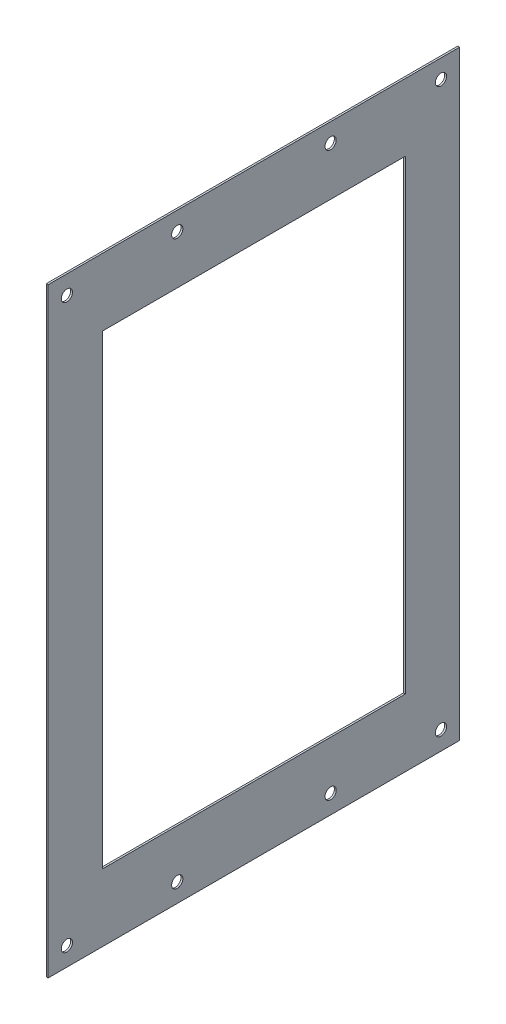
SolidWorks part; units mm, degrees
ref_plane "Front Plane" through (0, 0, 0) normal (1, 0, 0) x (0, 1, 0)
ref_plane "Top Plane" through (0, 0, 0) normal (0, 0, 1) x (0, 1, 0)
ref_plane "Right Plane" through (0, 0, 0) normal (0, 1, 0) x (-1, 0, 0)
sketch "Sketch1" plane through (0, 0, 0) normal (1, 0, 0) x (0, 1, 0)
  line L1 (-160.5, -110) -> (160.5, -110)
  line L2 (-160.5, -110) -> (-160.5, 110)
  line L3 (-160.5, 110) -> (160.5, 110)
  line L4 (160.5, -110) -> (160.5, 110)
  line L5 (-160.5, -110) -> (160.5, 110) construction
  line L6 (-160.5, 110) -> (160.5, -110) construction
  point P0 (0, 0)
  dimension "D1" = 321
  dimension "D2" = 220
extrude "Boss-Extrude1" add sketch "Sketch1" along normal blind 1
sketch "Sketch2" plane through (1, 0, 0) normal (1, 0, 0) x (0, 1, 0)
  line L0 (0, 110) -> (0, -110) construction
  line L1 (160.5, 110) -> (-160.5, 110) construction
  line L2 (-160.5, -110) -> (160.5, -110) construction
  line L4 (160.5, -110) -> (160.5, 110) construction
  line L5 (160.5, 0) -> (-160.5, 0) construction
  line L6 (-160.5, 110) -> (-160.5, -110) construction
  circle A0 centre (-150.5, 100) radius 3
  circle A1 centre (150.5, 100) radius 3
  circle A2 centre (-150.5, -100) radius 3
  circle A3 centre (150.5, -100) radius 3
  dimension "D1" = 6
  dimension "D2" = 10
  dimension "D3" = 10
extrude "Cut-Extrude1" cut sketch "Sketch2" against normal through all
sketch "Sketch3" plane through (1, 0, 0) normal (1, 0, 0) x (0, 1, 0)
  line L1 (-124.5, -81) -> (124.5, -81)
  line L2 (-124.5, -81) -> (-124.5, 81)
  line L3 (-124.5, 81) -> (124.5, 81)
  line L4 (124.5, -81) -> (124.5, 81)
  line L5 (-124.5, -81) -> (124.5, 81) construction
  line L6 (-124.5, 81) -> (124.5, -81) construction
  point P0 (0, 0)
  dimension "D1" = 249
  dimension "D2" = 162
extrude "Cut-Extrude2" cut sketch "Sketch3" against normal through all
sketch "Sketch4" plane through (1, 0, 0) normal (1, 0, 0) x (0, 1, 0)
  line L0 (0, 81) -> (0, -81) construction
  line L1 (124.5, 81) -> (-124.5, 81) construction
  line L2 (-124.5, -81) -> (124.5, -81) construction
  line L3 (-160.5, 110) -> (-160.5, -110) construction
  line L4 (124.5, -81) -> (124.5, 81) construction
  line L5 (124.5, 0) -> (-124.5, 0) construction
  line L6 (-124.5, 81) -> (-124.5, -81) construction
  circle A0 centre (-150.5, 41) radius 3
  circle A2 centre (150.5, 41) radius 3
  circle A3 centre (-150.5, -41) radius 3
  circle A4 centre (150.5, -41) radius 3
  dimension "D1" = 6
  dimension "D2" = 10
  dimension "D3" = 40
extrude "Cut-Extrude3" cut sketch "Sketch4" against normal through all
